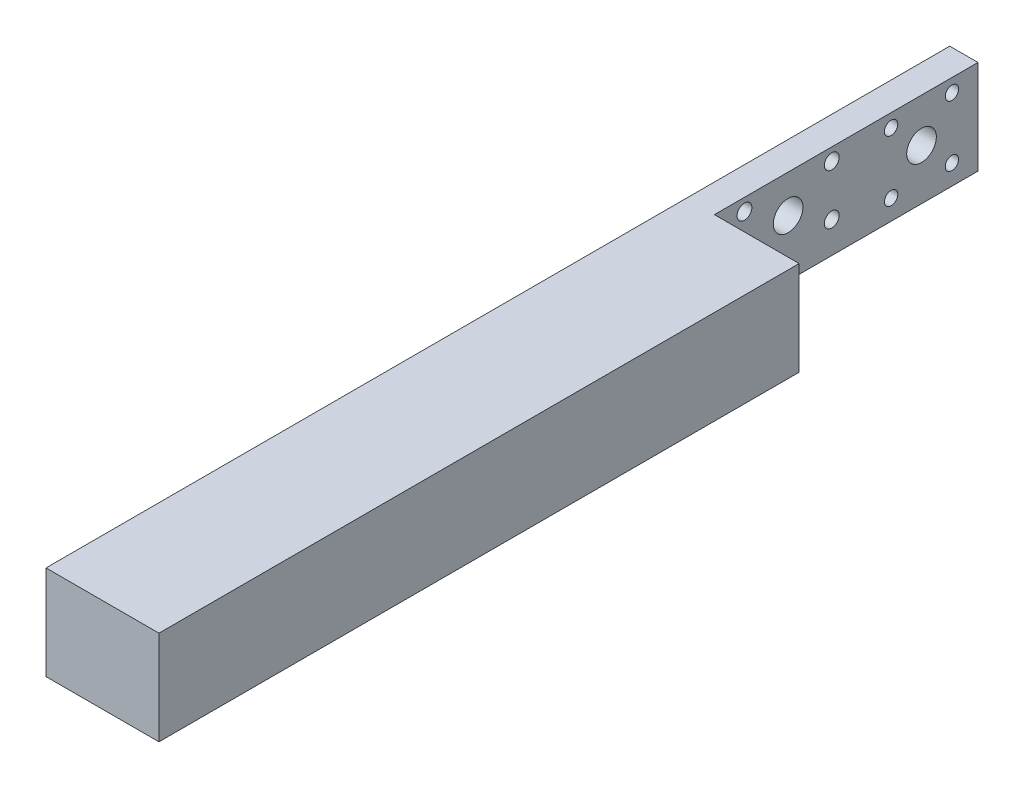
SolidWorks part; units mm, degrees
material "PE High Density"
ref_plane "Front Plane" through (0, 0, 0) normal (0, 0, 1) x (1, 0, 0)
ref_plane "Top Plane" through (0, 0, 0) normal (0, 1, 0) x (1, 0, 0)
ref_plane "Right Plane" through (0, 0, 0) normal (1, 0, 0) x (0, 0, -1)
sketch "Sketch1" plane through (0, 0, 0) normal (0, 0, 1) x (1, 0, 0)
  line L1 (-19.05, 19.05) -> (19.05, 19.05)
  line L2 (-19.05, 19.05) -> (-19.05, -19.05)
  line L3 (-19.05, -19.05) -> (19.05, -19.05)
  line L4 (19.05, 19.05) -> (19.05, -19.05)
  line L5 (-19.05, 19.05) -> (19.05, -19.05) construction
  line L6 (-19.05, -19.05) -> (19.05, 19.05) construction
  point P0 (0, 0)
  dimension "D1" = 38.1
  dimension "D2" = 38.1
extrude "Boss-Extrude1" add sketch "Sketch1" along normal blind 304.8
sketch "Sketch2" plane through (19.05, 0, 0) normal (1, 0, 0) x (0, 0, -1)
  line L0 (-304.8, 0) -> (0, 0) construction
  line L1 (-304.8, -19.05) -> (-304.8, 19.05) construction
  line L2 (0, -19.05) -> (0, 19.05) construction
  circle A0 centre (-19.05, -2) radius 5
  circle A1 centre (-64.05, 0) radius 5
  dimension "D1" = 10
  dimension "D2" = 45
  dimension "D3" = 19.05
  dimension "D4" = 2
extrude "Cut-Extrude1" cut sketch "Sketch2" against normal through all
sketch "Sketch4" plane through (19.05, 0, 0) normal (1, 0, 0) x (0, 0, -1)
  line L1 (-64.0501, 16.9959) -> (-78.7689, 8.4979) construction
  line L2 (-78.7689, 8.4979) -> (-78.7688, -8.498) construction
  line L3 (-78.7688, -8.498) -> (-64.0499, -16.9959) construction
  line L4 (-64.0499, -16.9959) -> (-49.3311, -8.4979) construction
  line L5 (-49.3311, -8.4979) -> (-49.3312, 8.498) construction
  line L6 (-49.3312, 8.498) -> (-64.0501, 16.9959) construction
  circle A0 centre (-64.05, 0) radius 17 construction
  circle A2 centre (-64.05, 0) radius 14.7188 construction
  circle A3 centre (-78.7689, 8.4979) radius 2.5
  dimension "D1" = 34
  dimension "D3" = 5
extrude "Cut-Extrude3" cut sketch "Sketch4" against normal through all
pattern_circular "CirPattern2" count 6 over 360 about axis through (0, 0, 64.05) along (1, 0, 0) skipping 2, 5 of "Cut-Extrude3"
sketch "Sketch5" plane through (19.05, 0, 0) normal (1, 0, 0) x (0, 0, -1)
  line L1 (-29.303, -12.253) -> (-8.797, -12.253) construction
  line L2 (-29.303, -12.253) -> (-29.303, 8.253) construction
  line L3 (-29.303, 8.253) -> (-8.797, 8.253) construction
  line L4 (-8.797, -12.253) -> (-8.797, 8.253) construction
  line L5 (-29.303, -12.253) -> (-8.797, 8.253) construction
  line L6 (-29.303, 8.253) -> (-8.797, -12.253) construction
  line L7 (-304.8, 19.05) -> (0, 19.05) construction
  circle A0 centre (-29.303, 8.253) radius 2.25
  point P0 (-19.05, -2)
  dimension "D2" = 4.5
  dimension "D1" = 29
extrude "Cut-Extrude4" cut sketch "Sketch5" against normal through all
pattern_circular "CirPattern3" count 4 over 360 about axis through (0, -2, 19.05) along (1, 0, 0) of "Cut-Extrude4"
sketch "Sketch6" plane through (19.05, 0, 0) normal (1, 0, 0) x (0, 0, -1)
  line L0 (-304.8, -19.05) -> (0, -19.05) construction
  line L1 (0, 19.05) -> (-88.9, 19.05)
  line L2 (0, 19.05) -> (0, -19.05)
  line L3 (0, -19.05) -> (-88.9, -19.05)
  line L4 (-88.9, 19.05) -> (-88.9, -19.05)
  dimension "D1" = 88.9
extrude "Cut-Extrude5" cut sketch "Sketch6" against normal blind 28.575
sketch "Sketch7" plane through (0, 0, 304.8) normal (0, 0, 1) x (1, 0, 0)
  line L0 (-19.05, 19.05) -> (-19.05, -19.05) construction
  line L1 (19.05, 19.05) -> (-19.05, 19.05)
  line L2 (19.05, 19.05) -> (19.05, 12.7)
  line L3 (19.05, 12.7) -> (-19.05, 12.7)
  line L4 (-19.05, 19.05) -> (-19.05, 12.7)
  dimension "D1" = 6.35
extrude "Cut-Extrude6" cut sketch "Sketch7" against normal through all
